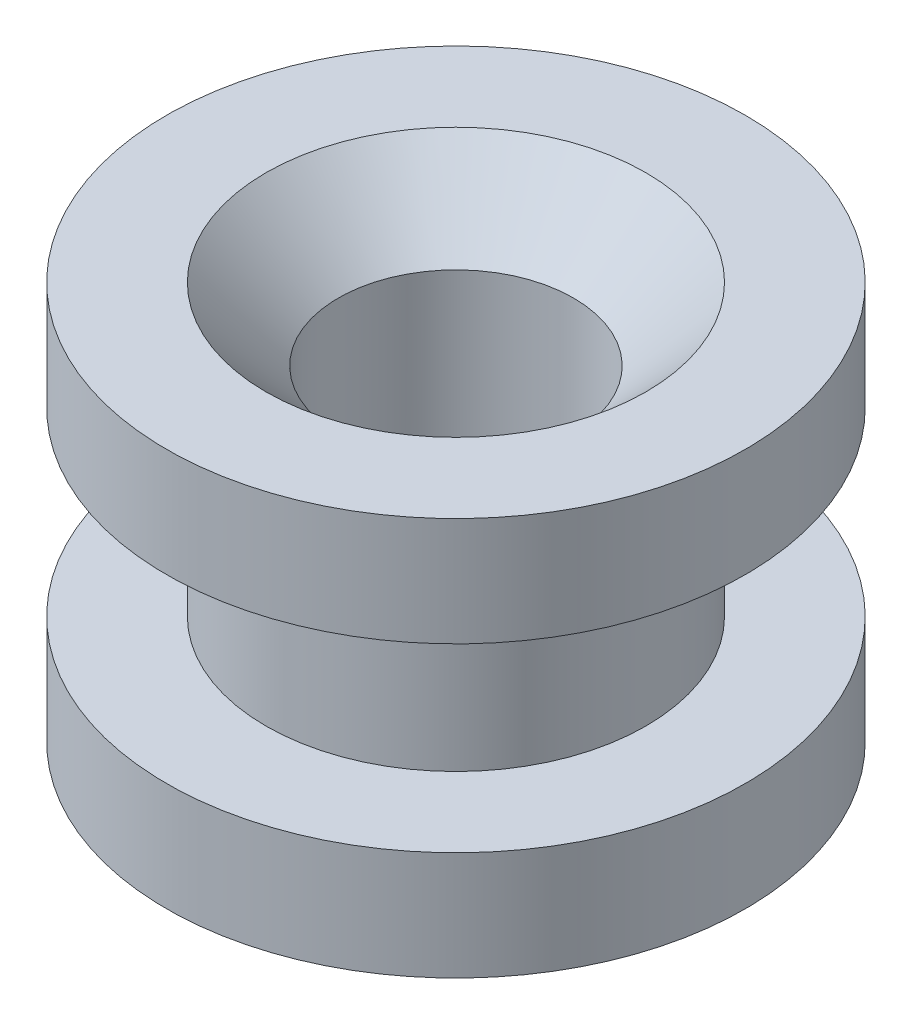
SolidWorks part; units mm, degrees
ref_plane "Front Plane" through (0, 0, 0) normal (0, 0, 1) x (1, 0, 0)
ref_plane "Top Plane" through (0, 0, 0) normal (0, 1, 0) x (1, 0, 0)
ref_plane "Right Plane" through (0, 0, 0) normal (1, 0, 0) x (0, 0, -1)
sketch "Sketch1" plane through (0, 0, 0) normal (0, 0, 1) x (1, 0, 0)
  line L0 (3.25, 0) -> (3.25, 11)
  line L1 (3.25, 11) -> (8, 11)
  line L2 (8, 11) -> (8, 8)
  line L3 (8, 8) -> (5.25, 8)
  line L4 (5.25, 8) -> (5.25, 3)
  line L5 (5.25, 3) -> (8, 3)
  line L6 (8, 3) -> (8, 0)
  line L7 (8, 0) -> (3.25, 0)
  line L8 (0, 0) -> (0, 17.7633) construction
  line L9 (0, 0) -> (-2.3464, 0) construction
  dimension "D1" = 3.25
  dimension "D2" = 8
  dimension "D3" = 11
  dimension "D4" = 3
  dimension "D5" = 3
  dimension "D6" = 2
revolve "Revolve1" add sketch "Sketch1" angle 360 about L8
chamfer "Chamfer1" distance 2 angle 45 2 edges at (0, 0, -3.25) (0, 11, -3.25)
